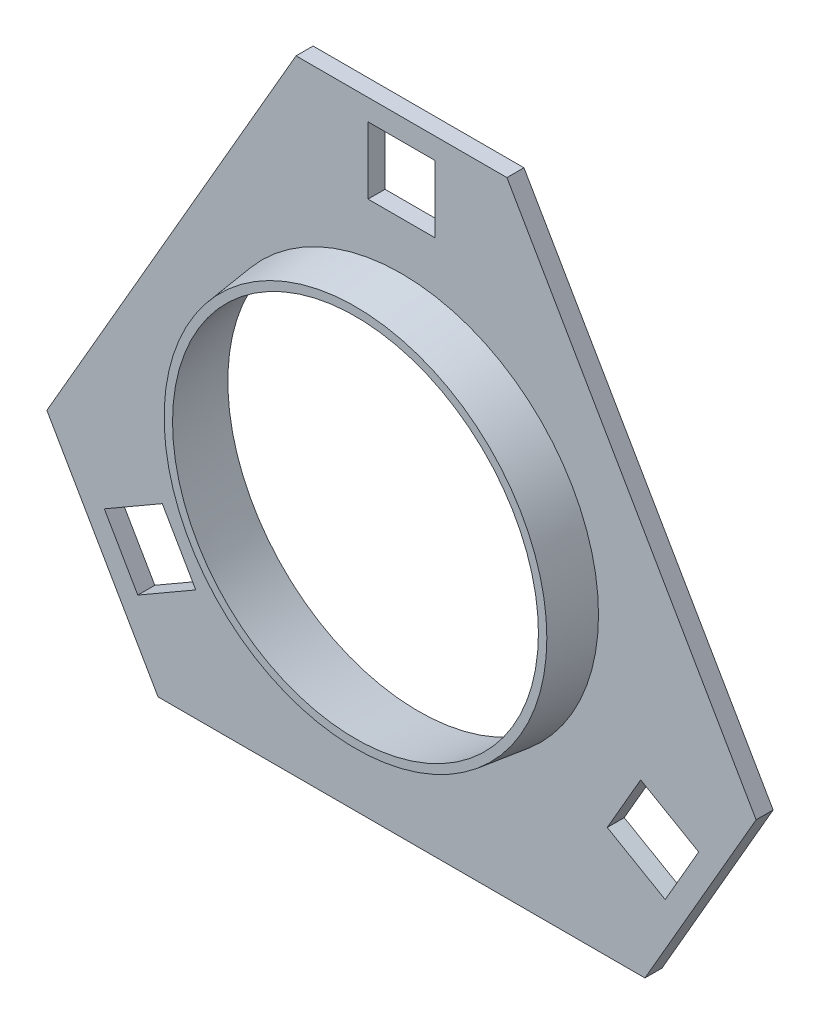
SolidWorks part; units mm, degrees
ref_plane "Front Plane" through (0, 0, 0) normal (0, 0, 1) x (1, 0, 0)
ref_plane "Top Plane" through (0, 0, 0) normal (0, 1, 0) x (1, 0, 0)
ref_plane "Right Plane" through (0, 0, 0) normal (1, 0, 0) x (0, 0, -1)
sketch "Sketch1" plane through (0, 0, 0) normal (0, 0, 1) x (1, 0, 0)
  line L0 (-31.75, 0) -> (31.75, 0)
  line L1 (31.75, 0) -> (46.25, 25.1147)
  line L2 (46.25, 25.1147) -> (13.75, 81.4064)
  line L3 (13.75, 81.4064) -> (-13.75, 81.4064)
  line L4 (-34.3926, 10.1772) -> (-38.7576, 17.7376)
  line L5 (-4.365, 78.6464) -> (4.365, 78.6464)
  line L6 (4.365, 78.6464) -> (4.365, 69.9164)
  line L7 (4.365, 69.9164) -> (-4.365, 69.9164)
  line L8 (-26.8322, 14.5422) -> (-34.3926, 10.1772)
  line L9 (34.3926, 10.1772) -> (38.7576, 17.7376)
  line L10 (38.7576, 17.7376) -> (31.1972, 22.1026)
  line L11 (31.1972, 22.1026) -> (26.8322, 14.5422)
  line L13 (26.8322, 14.5422) -> (34.3926, 10.1772)
  line L16 (-31.1972, 22.1026) -> (-26.8322, 14.5422)
  line L17 (-38.7576, 17.7376) -> (-31.1972, 22.1026)
  line L18 (-31.75, 0) -> (-46.25, 25.1147)
  line L19 (-46.25, 25.1147) -> (-13.75, 81.4064)
  line L20 (-4.365, 78.6464) -> (-4.365, 69.9164)
  point P24 (0, 69.9164)
extrude "Boss-Extrude1" add sketch "Sketch1" along normal blind 2.22
sketch "Sketch2" plane through (0, 0, 2.22) normal (0, 0, 1) x (1, 0, 0)
  circle A0 centre (0, 38) radius 25.695
extrude "Boss-Extrude2" add sketch "Sketch2" along normal blind 6 draft 7
sketch "Sketch3" plane through (0, 0, 8.22) normal (0, 0, 1) x (1, 0, 0)
  circle A1 centre (0, 38) radius 23.86
extrude "Cut-Extrude1" cut sketch "Sketch3" against normal blind 8.22 draft 7 draft outward yes
